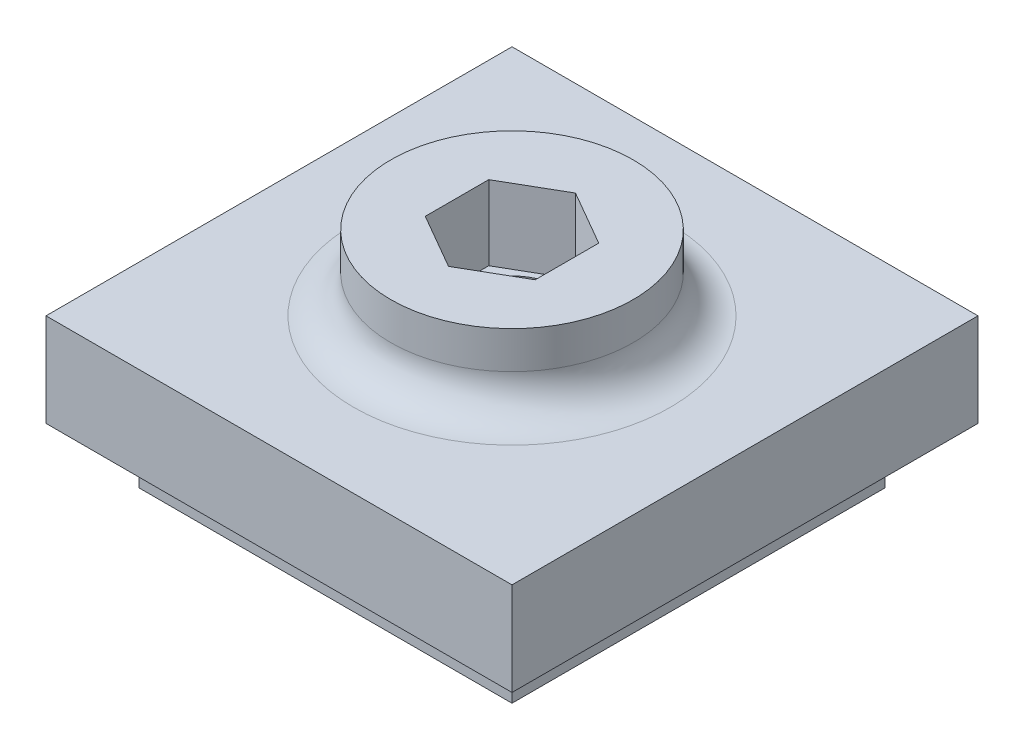
SolidWorks part; units mm, degrees
ref_plane "Front Plane" through (0, 0, 0) normal (0, 0, 1) x (1, 0, 0)
ref_plane "Top Plane" through (0, 0, 0) normal (0, 1, 0) x (1, 0, 0)
ref_plane "Right Plane" through (0, 0, 0) normal (1, 0, 0) x (0, 0, -1)
sketch "Sketch1" plane through (0, 0, 0) normal (0, 1, 0) x (1, 0, 0)
  line L0 (-12.5, 45) -> (-21.5, 45)
  line L1 (-12.5, 45) -> (-12.5, -135)
  line L2 (-12.5, -135) -> (-21.5, -135)
  line L3 (-21.5, 45) -> (-21.5, -135)
  line L4 (-12.5, 0) -> (12.5, 0) construction
  line L5 (-12.5, 10) -> (-15.5, 10)
  line L6 (-12.5, 10) -> (-12.5, -10)
  line L7 (-12.5, -10) -> (-15.5, -10)
  line L8 (-15.5, 10) -> (-15.5, -10)
  line L9 (-12.5, -15) -> (-8.5, -15)
  line L10 (-12.5, -15) -> (-12.5, 15)
  line L11 (-12.5, 15) -> (-8.5, 15)
  line L12 (-8.5, -15) -> (-8.5, 15)
  line L13 (-8.5, 12.5) -> (12.5, 12.5)
  line L14 (-8.5, 12.5) -> (-8.5, -12.5)
  line L15 (-8.5, -12.5) -> (12.5, -12.5)
  line L16 (12.5, 12.5) -> (12.5, -12.5)
  line L17 (-12.5, -12.5) -> (-12.5, 12.5)
  line L18 (-10, -10) -> (10, -10)
  line L19 (-10, -10) -> (-10, 10)
  line L20 (-10, 10) -> (10, 10)
  line L21 (10, -10) -> (10, 10)
  line L22 (-10, -10) -> (10, 10) construction
  line L23 (-10, 10) -> (10, -10) construction
  line L24 (-12.5, 12.5) -> (12.5, 12.5)
  line L25 (12.5, -12.5) -> (12.5, 12.5)
  line L26 (-12.5, -12.5) -> (12.5, -12.5)
  line L27 (2.95, 1.7032) -> (0, 3.4064)
  line L28 (2.75, 1.5877) -> (0, 3.1754) construction
  line L29 (0, 3.1754) -> (-2.75, 1.5877) construction
  line L30 (-2.75, 1.5877) -> (-2.75, -1.5877) construction
  line L31 (-2.75, -1.5877) -> (0, -3.1754) construction
  line L32 (0, -3.1754) -> (2.75, -1.5877) construction
  line L33 (2.75, -1.5877) -> (2.75, 1.5877) construction
  line L34 (0, 3.4064) -> (-2.95, 1.7032)
  line L35 (-2.95, 1.7032) -> (-2.95, -1.7032)
  line L36 (-2.95, -1.7032) -> (0, -3.4064)
  line L37 (0, -3.4064) -> (2.95, -1.7032)
  line L38 (2.95, -1.7032) -> (2.95, 1.7032)
  circle A0 centre (0, 0) radius 2.5
  circle A1 centre (0, 0) radius 6.5
  circle A2 centre (0, 0) radius 2.75 construction
  point P21 (0, 0)
sketch "Sketch2" plane through (0, 0, 0) normal (0, 1, 0) x (1, 0, 0)
  line L4 (-12.5, 12.5) -> (12.5, 12.5) construction
  line L5 (12.5, -12.5) -> (12.5, 12.5) construction
  line L6 (-12.5, -12.5) -> (12.5, -12.5) construction
  line L7 (-12.5, -12.5) -> (-12.5, 12.5) construction
  line L8 (-8.5, 12.5) -> (12.5, 12.5) construction
  line L9 (12.5, 12.5) -> (12.5, -12.5) construction
  line L10 (-8.5, -12.5) -> (12.5, -12.5) construction
  line L16 (-12.5, 12.5) -> (12.5, 12.5)
  line L17 (12.5, -12.5) -> (12.5, 12.5)
  line L18 (-12.5, -12.5) -> (12.5, -12.5)
  line L19 (-12.5, -12.5) -> (-12.5, 12.5)
  line L20 (-8.5, 12.5) -> (12.5, 12.5)
  line L21 (12.5, 12.5) -> (12.5, -12.5)
  line L22 (-8.5, -12.5) -> (12.5, -12.5)
extrude "Boss-Extrude1" add sketch "Sketch2" along normal blind 5 contours L19 L18 L17 L16
sketch "Sketch3" plane through (0, 0, 0) normal (0, -1, 0) x (1, 0, 0)
  line L0 (-10, 10) -> (10, 10) construction
  line L1 (10, 10) -> (10, -10) construction
  line L2 (-10, -10) -> (10, -10) construction
  line L3 (-10, 10) -> (-10, -10) construction
  line L4 (-10, 10) -> (10, 10)
  line L5 (10, 10) -> (10, -10)
  line L6 (-10, -10) -> (10, -10)
  line L7 (-10, 10) -> (-10, -10)
extrude "Boss-Extrude2" add sketch "Sketch3" along normal blind 3
sketch "Sketch4" plane through (0, 5, 0) normal (0, 1, 0) x (1, 0, 0)
  circle A0 centre (0, 0) radius 6.5 construction
  circle A1 centre (0, 0) radius 6.5
extrude "Boss-Extrude3" add sketch "Sketch4" along normal blind 4
sketch "Sketch5" plane through (0, 9, 0) normal (0, 1, 0) x (1, 0, 0)
  circle A0 centre (0, 0) radius 2.5 construction
  circle A1 centre (0, 0) radius 2.5 construction
  circle A2 centre (0, 0) radius 2.62
  dimension "D1" = 0.12
extrude "Cut-Extrude1" cut sketch "Sketch5" against normal through all both and the other way through all
sketch "Sketch6" plane through (0, 9, 0) normal (0, 1, 0) x (1, 0, 0)
  line L0 (0, 3.4064) -> (-2.95, 1.7032) construction
  line L1 (-2.95, 1.7032) -> (-2.95, -1.7032) construction
  line L2 (-2.95, -1.7032) -> (0, -3.4064) construction
  line L3 (0, -3.4064) -> (2.95, -1.7032) construction
  line L4 (2.95, -1.7032) -> (2.95, 1.7032) construction
  line L5 (2.95, 1.7032) -> (0, 3.4064) construction
  line L6 (0, 3.4064) -> (-2.95, 1.7032)
  line L7 (-2.95, 1.7032) -> (-2.95, -1.7032)
  line L8 (-2.95, -1.7032) -> (0, -3.4064)
  line L9 (0, -3.4064) -> (2.95, -1.7032)
  line L10 (2.95, -1.7032) -> (2.95, 1.7032)
  line L11 (2.95, 1.7032) -> (0, 3.4064)
extrude "Cut-Extrude2" cut sketch "Sketch6" against normal up to surface (4 mm away) up to face at (0, 5, 6.5)
fillet "Fillet1" radius 2 1 edges at (0, 5, 6.5)
sketch "Nut holder" plane through (0, 9, 0) normal (0, 1, 0) x (1, 0, 0)
  line L0 (0, 3.4064) -> (-2.95, 1.7032) construction
  line L1 (0, 3.4064) -> (-2.95, 1.7032)
  line L2 (-2.95, 1.7032) -> (-2.95, -1.7032) construction
  line L3 (-2.95, -1.7032) -> (0, -3.4064) construction
  line L4 (0, -3.4064) -> (2.95, -1.7032) construction
  line L5 (2.95, 1.7032) -> (2.95, -1.7032) construction
  line L6 (0, 3.4064) -> (2.95, 1.7032) construction
  line L7 (-2.95, 1.7032) -> (-2.95, -1.7032)
  line L8 (-2.95, -1.7032) -> (0, -3.4064)
  line L9 (0, -3.4064) -> (2.95, -1.7032)
  line L10 (2.95, 1.7032) -> (2.95, -1.7032)
  line L11 (0, 3.4064) -> (2.95, 1.7032)
  circle A0 centre (0, 0) radius 2.62 construction
  circle A1 centre (0, 0) radius 6.5
  circle A2 centre (0, 0) radius 6.5
  circle A3 centre (0, 0) radius 2.62 construction
  circle A4 centre (0, 0) radius 2.5
  circle A5 centre (0, 6.5) radius 1
  dimension "D3" = 2
  dimension "D1" = 0
  dimension "D2" = 0.12
